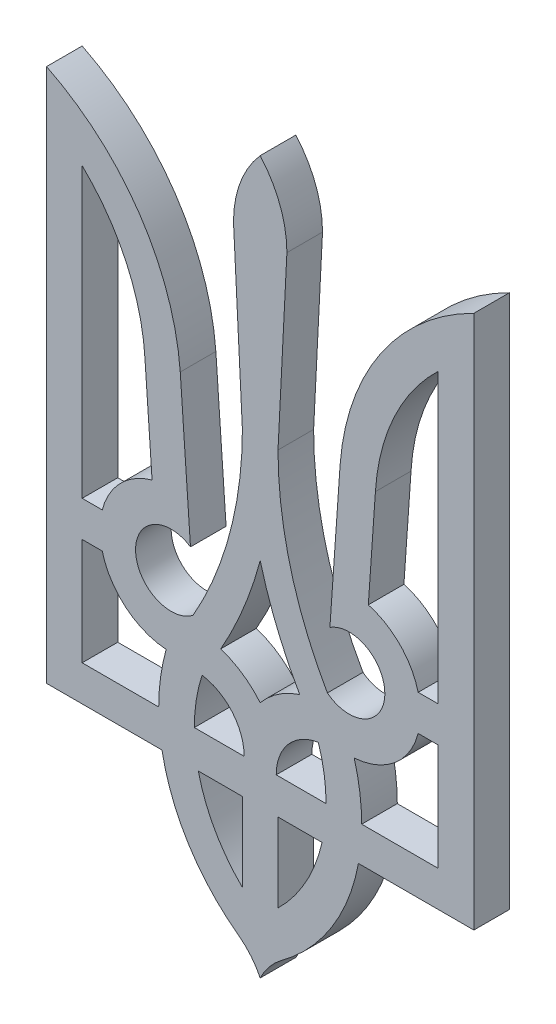
SolidWorks part; units mm, degrees
ref_plane "Спереди" through (0, 0, 0) normal (0, 0, 1) x (1, 0, 0)
ref_plane "Сверху" through (0, 0, 0) normal (0, 1, 0) x (1, 0, 0)
ref_plane "Справа" through (0, 0, 0) normal (1, 0, 0) x (0, 0, -1)
sketch "Эскиз1" plane through (0, 0, 0) normal (0, 0, 1) x (1, 0, 0)
  line L0 (0, 0) -> (-60, 0) construction
  line L1 (0, 0) -> (0, -45) construction
  line L2 (-27.5833, -45) -> (-60, -45)
  line L3 (-60, -45) -> (-60, 105)
  line L4 (-22.4495, 49.493) -> (-19.5761, 8.4012)
  line L5 (-22.38, 48.4989) -> (-20.3847, 19.9658) construction
  line L6 (0, 0) -> (15, 0) construction
  line L7 (0, -35) -> (26.5, -35) construction
  line L8 (0, -35) -> (-50, -35) construction
  line L9 (-28.5, -35) -> (-50, -35)
  line L10 (-50, -35) -> (-50, -5)
  line L11 (-50, 5) -> (-50, 85.9092)
  line L12 (-60, -45) -> (-90, -45) construction
  line L13 (-50, -35) -> (-50, 105) construction
  line L14 (-90, -45) -> (-90, 44.25) construction
  line L15 (0, 0) -> (0, 129.6666) construction
  line L16 (-60, 0) -> (-25, 0) construction
  line L17 (-44.3649, 5) -> (-50, 5)
  line L18 (-32.3556, 47.8014) -> (-30.3604, 19.2683)
  line L19 (-44.3649, -5) -> (-50, -5)
  line L20 (0, -45) -> (0, -95.3664) construction
  line L21 (-5, -67.1364) -> (-5, -45)
  line L22 (0, -45) -> (-60, -45) construction
  line L23 (-5, -45) -> (-17.3748, -45)
  line L24 (-18.5, -35) -> (-4.5, -35)
  line L25 (0, -45) -> (60, -45) construction
  line L26 (60, -45) -> (60, 93.5) construction
  line L27 (60, 93.5) -> (22.5, 93.5) construction
  line L28 (-90, 44.25) -> (-110, 44.25) construction
  line L29 (-7.5, 93.5) -> (0, 93.5) construction
  line L30 (-5, 44.25) -> (-7.5, 93.5)
  line L31 (0, -95.3664) -> (-18.004, -95.3664) construction
  line L32 (0, 113.3431) -> (0, -86.6569)
  arc A0 (-22.4495, 49.493) -> (-60, 105) centre (-90, 44.25) ccw
  arc A1 (-50, 85.9092) -> (-32.3556, 47.8014) centre (-90, 44.25) cw
  arc A2 (-44.3649, -5) -> (-26.4011, -19.9509) centre (-25, 0) ccw
  arc A3 (-19.5761, 8.4012) -> (-18.8639, -7.8961) centre (-25, 0) ccw
  arc A4 (-26.4011, -19.9509) -> (-28.5, -35) centre (26.5, -35) ccw
  arc A5 (-18.5, -35) -> (-16.3222, -21.1704) centre (26.5, -35) cw
  arc A6 (-27.5833, -45) -> (-5.9458, -79.4103) centre (26.5, -35) ccw
  arc A7 (-30.3604, 19.2683) -> (-44.3649, 5) centre (-25, 0) ccw
  arc A8 (-17.3748, -45) -> (-5, -67.1364) centre (26.5, -35) ccw
  arc A9 (-4.5, -35) -> (-16.3222, -21.1704) centre (-18.5, -35) ccw
  arc A10 (0, 113.3431) -> (-7.5, 93.5) centre (22.5, 93.5) ccw
  arc A11 (-18.8639, -7.8961) -> (-5, 44.25) centre (-110, 44.25) ccw
  arc A12 (0, -86.6569) -> (-5.9458, -79.4103) centre (-18.004, -95.3664) ccw
  arc A14 (0, -19.7111) -> (-11.0914, -12.1721) centre (-18.5, -35) ccw
  arc A16 (-11.0914, -12.1721) -> (0, 14.8157) centre (-110, 44.25) ccw
  point P3 (0, 5)
  point P7 (-87.4973, 5)
  point P8 (260.5938, -135.0208)
  point P9 (-87.4973, -5)
  point P26 (-19.6695, 9.7374)
  point P27 (-32.4251, 48.7954)
  point P28 (-29.6451, 9.0398)
  dimension "D9" = 135.5074
  dimension "D10" = 10
  dimension "D11" = 35
  dimension "D12" = 40
  dimension "D13" = 20
  dimension "D19" = 26.5
  dimension "D20" = 113.87
  dimension "D22" = 10
  dimension "D23" = 45
  dimension "D24" = 45
  dimension "D25" = 28
  dimension "D29" = 60
  dimension "D31" = 210
  dimension "D34" = 18.004
  dimension "D35" = 48
  dimension "D33" = 200
  dimension "D21" = 40
  dimension "D1" = 120
  dimension "D2" = 45
  dimension "D3" = 5
  dimension "D4" = 150
  dimension "D5" = 5
  dimension "D7" = 30
  dimension "D8" = 89.25
  dimension "D14" = 4
  dimension "D15" = 60.7207
  dimension "D17" = 21.5
  dimension "D18" = 15
  dimension "D26" = 60
  dimension "D27" = 138.5
  dimension "D28" = 37.5
  dimension "D30" = 20
  dimension "D32" = 7.5
  dimension "D36" = 200
  dimension "D6" = 10
  dimension "D16" = 10
extrude "Бобышка-Вытянуть1" add sketch "Эскиз1" along normal blind 10 contours A14 A16 L32 A10 L30 A11 A3 L4 A0 L3 L2 A6 A12 L18 A7 L17 L11 A1 A2 A4 L9 L10 L19 A8 L23 L21 A9 L24 A5
mirror "Зеркальное отражение1" about plane through (0, 0, 0) normal (1, 0, 0) of "Бобышка-Вытянуть1"
scale "Масштаб1" [suppressed]
sketch "Эскиз2" [suppressed] plane through (0, 0, 7.475) normal (0, 0, 1) x (1, 0, 0)
  line L0 (-1.0178, 25.4814) -> (1.0178, 25.4814) construction
  arc A0 (0, 27.4814) -> (-1.125, 24.505) centre (3.375, 24.505) ccw construction
  arc A1 (1.125, 24.505) -> (0, 27.4814) centre (-3.375, 24.505) ccw construction
  circle A2 centre (0, 25.4814) radius 0.5
  dimension "D1" = 1
  dimension "D2" = 2
extrude "Вырез-Вытянуть1" [suppressed] cut sketch "Эскиз2" against normal through all
